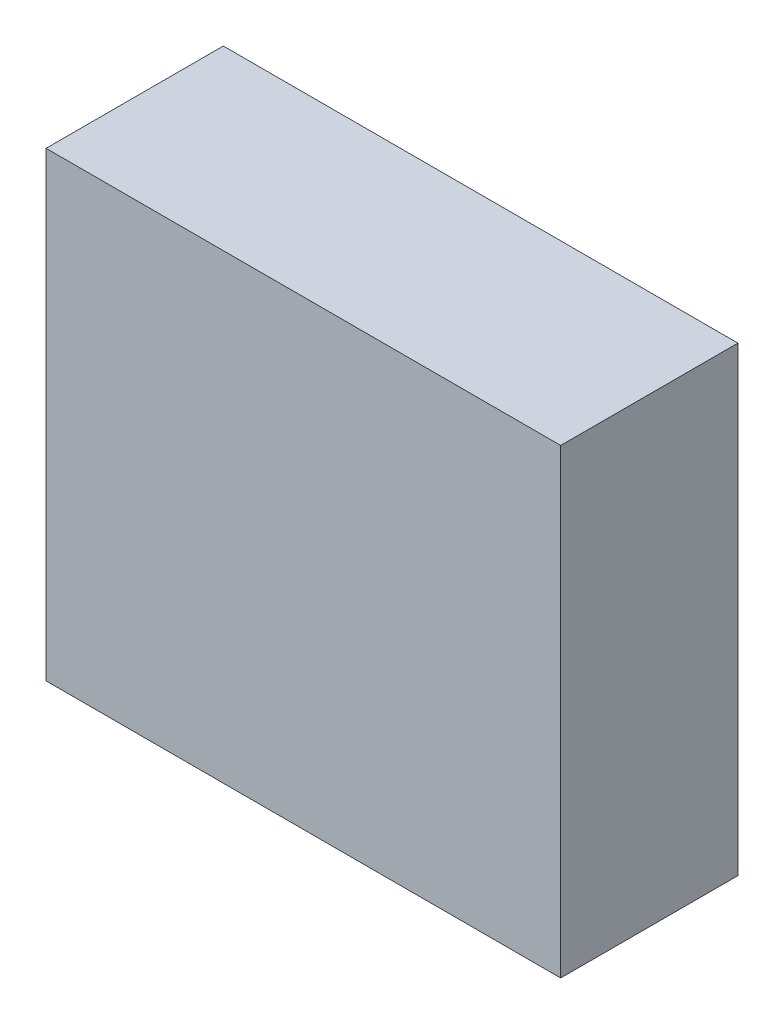
SolidWorks part; units mm, degrees
ref_plane "Plan de face" through (0, 0, 0) normal (0, 0, 1) x (1, 0, 0)
ref_plane "Plan de dessus" through (0, 0, 0) normal (0, 1, 0) x (1, 0, 0)
ref_plane "Plan de droite" through (0, 0, 0) normal (1, 0, 0) x (0, 0, -1)
sketch "Esquisse1" plane through (0, 0, 0) normal (0, 0, 1) x (1, 0, 0)
  line L1 (0, 0) -> (45.3, 0)
  line L2 (0, 0) -> (0, 40.6)
  line L3 (0, 40.6) -> (45.3, 40.6)
  line L4 (45.3, 0) -> (45.3, 40.6)
  dimension "D1" = 45.3
  dimension "D2" = 40.6
extrude "Boss.-Extru.1" add sketch "Esquisse1" along normal blind 15.6
